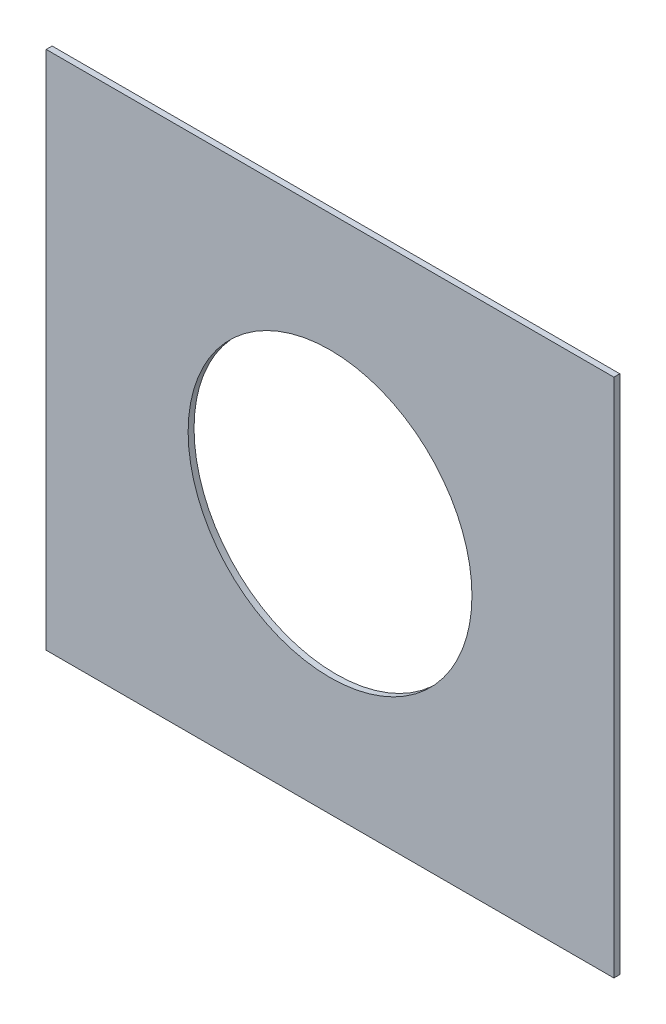
SolidWorks part; units mm, degrees
material "Al homeycomb"
ref_plane "Front Plane" through (0, 0, 0) normal (0, 0, 1) x (1, 0, 0)
ref_plane "Top Plane" through (0, 0, 0) normal (0, 1, 0) x (1, 0, 0)
ref_plane "Right Plane" through (0, 0, 0) normal (1, 0, 0) x (0, 0, -1)
sketch "Sketch1" plane through (0, 0, 0) normal (0, 0, 1) x (1, 0, 0)
  line L1 (-1200, -1100) -> (1200, -1100)
  line L2 (-1200, -1100) -> (-1200, 1100)
  line L3 (-1200, 1100) -> (1200, 1100)
  line L4 (1200, -1100) -> (1200, 1100)
  line L5 (-1200, -1100) -> (1200, 1100) construction
  line L6 (-1200, 1100) -> (1200, -1100) construction
  point P0 (0, 0)
  dimension "D1" = 2400
  dimension "D2" = 2200
extrude "Boss-Extrude1" add sketch "Sketch1" along normal blind 25
sketch "Sketch2" plane through (0, 0, 25) normal (0, 0, 1) x (1, 0, 0)
  circle A0 centre (0, 0) radius 600
  dimension "D1" = 1200
extrude "Cut-Extrude1" cut sketch "Sketch2" against normal blind 32
